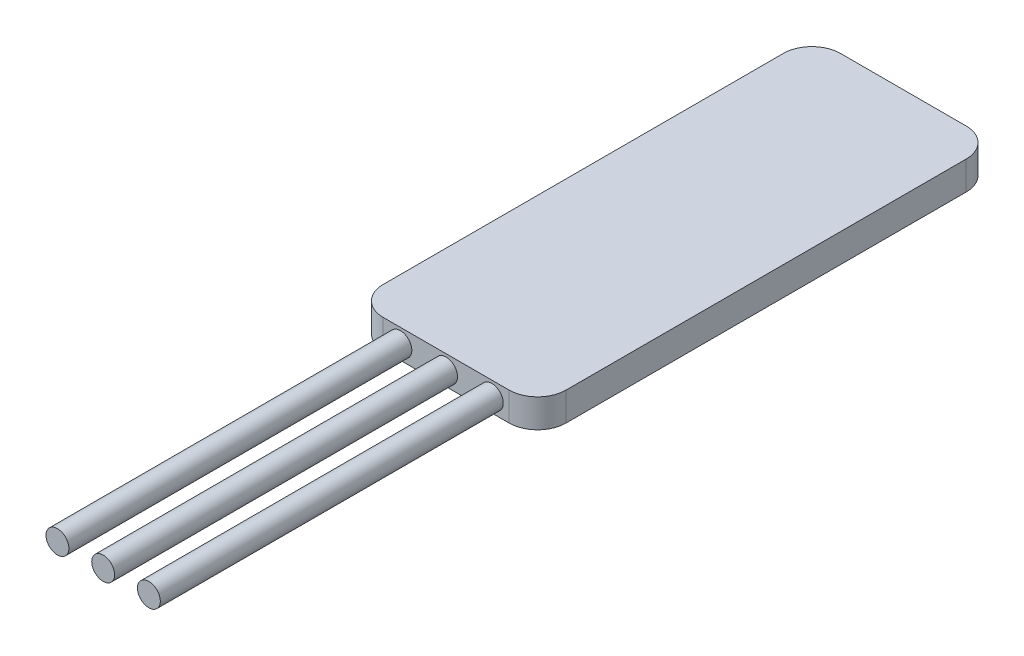
SolidWorks part; units mm, degrees
material "Silicon Rubber"
ref_plane "Front Plane" through (0, 0, 0) normal (0, 0, 1) x (1, 0, 0)
ref_plane "Top Plane" through (0, 0, 0) normal (0, 1, 0) x (1, 0, 0)
ref_plane "Right Plane" through (0, 0, 0) normal (1, 0, 0) x (0, 0, -1)
sketch "Sketch1" plane through (0, 0, 0) normal (0, 1, 0) x (1, 0, 0)
  line L1 (-3.2, 8) -> (3.2, 8)
  line L2 (-3.2, 8) -> (-3.2, -8)
  line L3 (-3.2, -8) -> (3.2, -8)
  line L4 (3.2, 8) -> (3.2, -8)
  line L5 (-3.2, 8) -> (3.2, -8) construction
  line L6 (-3.2, -8) -> (3.2, 8) construction
  point P0 (0, 0)
  dimension "D1" = 16
  dimension "D2" = 6.4
extrude "BASE" add sketch "Sketch1" along normal mid plane 1
fillet "BF" radius 1 4 edges at (-3.2, 0, -8) (3.2, 0, -8) (-3.2, 0, 8) (3.2, 0, 8)
sketch "Sketch2" plane through (0, 0, 8) normal (0, 0, 1) x (1, 0, 0)
  circle A0 centre (0, 0) radius 0.4
  point P2 (0, 0)
  dimension "D1" = 0.8
extrude "WIRE" add sketch "Sketch2" along normal blind 12
pattern_linear "WIRE LP" count 2 spacing 1.6 along (-1, 0, 0) count 2 spacing 1.6 along (1, 0, 0) of "WIRE"
